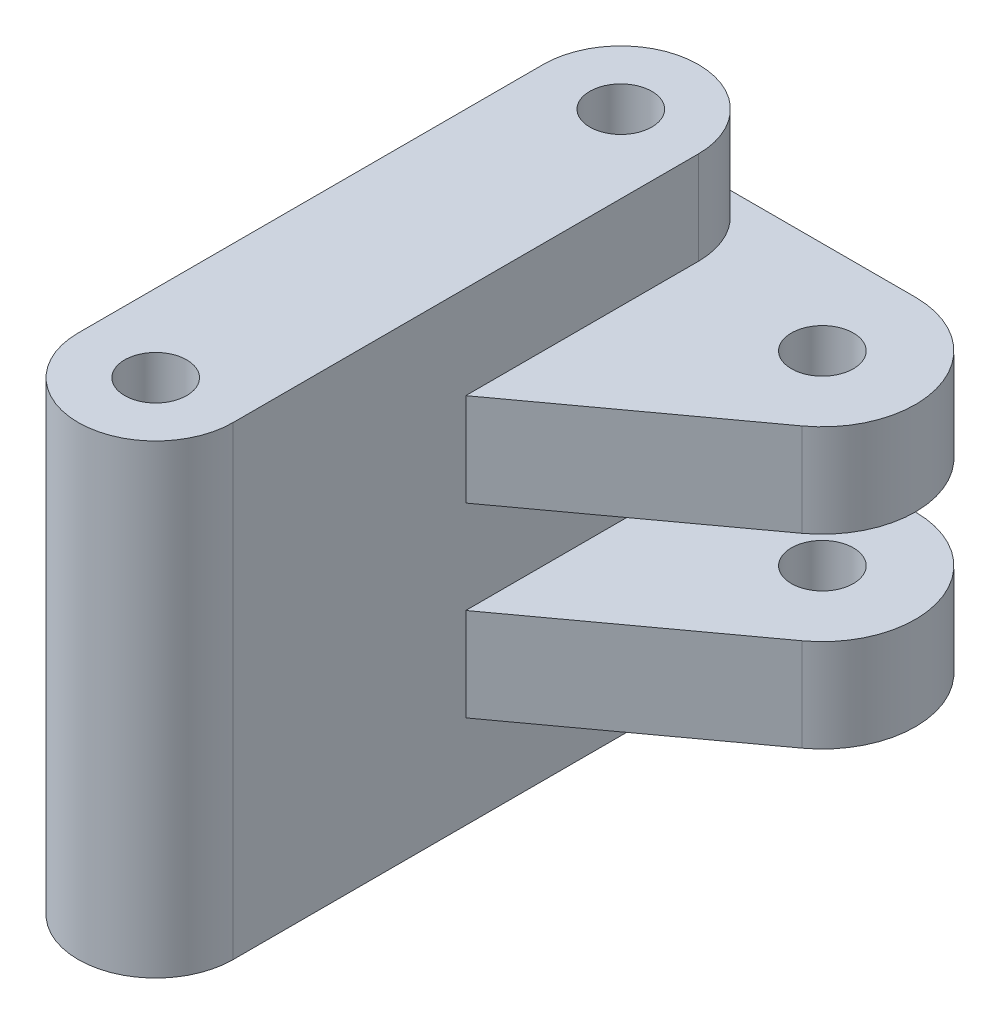
SolidWorks part; units mm, degrees
ref_plane "Alzado" through (0, 0, 0) normal (0, 0, 1) x (1, 0, 0)
ref_plane "Planta" through (0, 0, 0) normal (0, 1, 0) x (1, 0, 0)
ref_plane "Vista lateral" through (0, 0, 0) normal (1, 0, 0) x (0, 0, -1)
sketch "Croquis1" plane through (0, 0, 0) normal (0, 1, 0) x (1, 0, 0)
  line L0 (0, -7.5) -> (0, 7.5) construction
  line L1 (-2.5, -7.5) -> (-2.5, 7.5)
  line L2 (2.5, -7.5) -> (2.5, 7.5)
  arc A0 (-2.5, -7.5) -> (2.5, -7.5) centre (0, -7.5) ccw
  arc A1 (2.5, 7.5) -> (-2.5, 7.5) centre (0, 7.5) ccw
  circle A2 centre (0, 7.5) radius 1
  circle A3 centre (0, -7.5) radius 1
  point P2 (0, 0)
  dimension "D3" = 2
  dimension "D1" = 15
  dimension "D2" = 5
extrude "Saliente-Extruir1" add sketch "Croquis1" along normal blind 15
ref_plane "Plano3" through (0, 7.5, 0) normal (0, 1, 0) x (-1, 0, 0)
ref_plane "Plano1" through (0, 6, 0) normal (0, 1, 0) x (-1, 0, 0)
sketch "Croquis2" plane through (0, 6, 0) normal (0, 1, 0) x (-1, 0, 0)
  line L0 (-2.5, -7.5) -> (-2.5, 0)
  line L1 (-2.5, 7.5) -> (-2.5, -7.5) construction
  line L2 (-2.5, 0) -> (-8.769, -4.5771)
  line L3 (0, -10) -> (-7, -10)
  arc A1 (-2.5, -7.5) -> (0, -10) centre (0, -7.5) ccw
  arc A2 (-7, -10) -> (-8.769, -4.5771) centre (-7, -7) cw
  circle A3 centre (-7, -7) radius 1
  arc A4 (-2.5, -7.5) -> (2.5, -7.5) centre (0, -7.5) ccw construction
  dimension "D1" = 2
  dimension "D2" = 3
  dimension "D3" = 7
extrude "Saliente-Extruir2" add sketch "Croquis2" against normal blind 3
ref_plane "Plano2" through (0, 9, 0) normal (0, 1, 0) x (-1, 0, 0)
sketch "Croquis3" plane through (0, 9, 0) normal (0, 1, 0) x (-1, 0, 0)
  line L3 (-7, -10) -> (0, -10) construction
  line L4 (-2.5, 0) -> (-8.769, -4.5771) construction
  line L5 (-2.5, -7.5) -> (-2.5, 0) construction
  line L7 (-7, -10) -> (0, -10)
  line L8 (-2.5, 0) -> (-8.769, -4.5771)
  line L9 (-2.5, -7.5) -> (-2.5, 0)
  arc A3 (-2.5, -7.5) -> (0, -10) centre (0, -7.5) ccw construction
  arc A4 (-8.769, -4.5771) -> (-7, -10) centre (-7, -7) ccw construction
  circle A5 centre (-7, -7) radius 1 construction
  arc A7 (-2.5, -7.5) -> (0, -10) centre (0, -7.5) ccw
  arc A8 (-8.769, -4.5771) -> (-7, -10) centre (-7, -7) ccw
  circle A9 centre (-7, -7) radius 1
extrude "Saliente-Extruir3" add sketch "Croquis3" along normal blind 3
